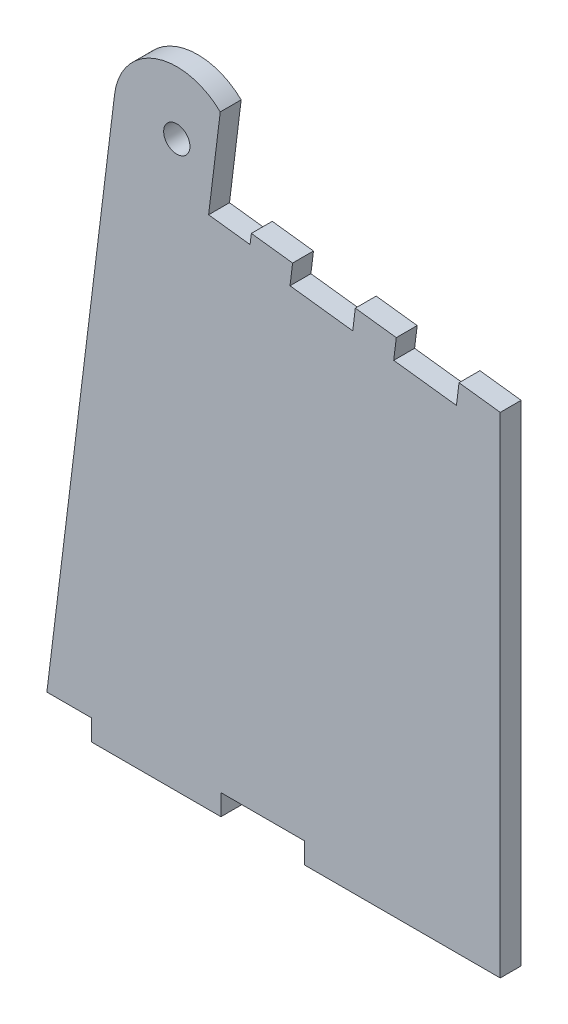
SolidWorks part; units mm, degrees
ref_plane "Front Plane" through (0, 0, 0) normal (0, 0, 1) x (1, 0, 0)
ref_plane "Top Plane" through (0, 0, 0) normal (0, 1, 0) x (1, 0, 0)
ref_plane "Right Plane" through (0, 0, 0) normal (1, 0, 0) x (0, 0, -1)
sketch "Sketch1" plane through (0, 0, 0) normal (0, 0, 1) x (1, 0, 0)
  line L0 (19.4741, 185.3905) -> (15.9319, 156.5422)
  line L1 (0, 0) -> (104.5562, 0)
  line L5 (16.6362, 157.6006) -> (19.7289, 182.7886) construction
  line L6 (26.0199, 176.1758) -> (23.8389, 158.4132) construction
  line L7 (-12.636, 173.9787) -> (-33.9979, 0)
  line L8 (0, 0) -> (-33.9979, 0)
  line L9 (28.9242, 158.1458) -> (104.5562, 148.8593)
  line L10 (23.8324, 158.7709) -> (109.1914, 148.2902) construction
  line L11 (15.9319, 156.5422) -> (28.5373, 154.9944)
  line L12 (28.5373, 154.9944) -> (28.9242, 158.1458)
  line L13 (104.5562, 148.8593) -> (104.5562, 0)
  line L14 (91.9509, 150.407) -> (91.177, 144.1044) construction
  line L15 (91.177, 144.1044) -> (72.269, 146.426) construction
  line L16 (72.269, 146.426) -> (73.0429, 152.7287) construction
  line L17 (66.7402, 153.5025) -> (63.029, 123.277) construction
  line L18 (92.0265, 150.3978) -> (91.2434, 144.0195)
  line L19 (91.2434, 144.0195) -> (72.1841, 146.3596)
  line L20 (72.1841, 146.3596) -> (72.9673, 152.7379)
  line L21 (41.4539, 156.6073) -> (40.6708, 150.229)
  line L22 (40.6708, 150.229) -> (59.73, 147.8888)
  line L23 (59.73, 147.8888) -> (60.5132, 154.2671)
  line L24 (-45.085, 0) -> (-45.085, 6.35)
  line L25 (-45.085, 6.35) -> (-19.685, 6.35)
  line L26 (-19.685, 6.35) -> (-19.685, 0)
  line L27 (0, 0) -> (0, 26.7667) construction
  line L28 (19.685, 6.35) -> (19.685, 0)
  line L29 (45.085, 6.35) -> (19.685, 6.35)
  line L30 (45.085, 0) -> (45.085, 6.35)
  circle A0 centre (6.272, 171.6571) radius 4 construction
  circle A1 centre (6.272, 171.6571) radius 4
  arc A2 (19.4741, 185.3905) -> (-12.636, 173.9787) centre (6.272, 171.6571) ccw
  dimension "D1" = 38.1
  dimension "D2" = 7.62
  dimension "D3" = 12.7
  dimension "D4" = 76.2
  dimension "D5" = 12.7
  dimension "D6" = 19.05
  dimension "D7" = 6.35
  dimension "D9" = 3.175
  dimension "D10" = 6.35
  dimension "D11" = 25.4
  dimension "D12" = 19.685
  dimension "D8" = 0.0762
extrude "Boss-Extrude1" add sketch "Sketch1" along normal blind 6.35 contours L0 A2 L7 L8 L1 L13 L9 L18 L19 L20 L23 L22 L21 L12 L11 A1
